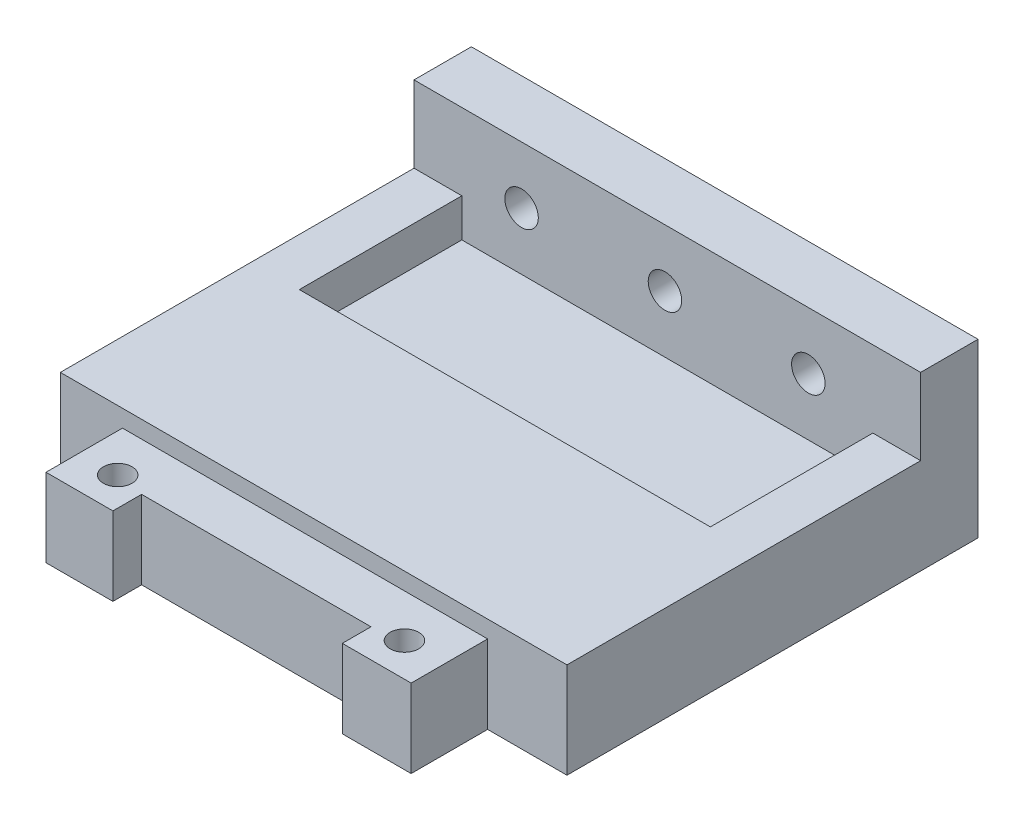
SolidWorks part; units mm, degrees
ref_plane "Front Plane" through (0, 0, 0) normal (0, 0, 1) x (1, 0, 0)
ref_plane "Top Plane" through (0, 0, 0) normal (0, 1, 0) x (1, 0, 0)
ref_plane "Right Plane" through (0, 0, 0) normal (1, 0, 0) x (0, 0, -1)
sketch "Sketch2" plane through (0, 0, 0) normal (0, 1, 0) x (1, 0, 0)
  line L1 (0, 0) -> (53, 0)
  line L2 (0, 0) -> (0, 43)
  line L3 (0, 43) -> (53, 43)
  line L4 (53, 0) -> (53, 43)
  dimension "D1" = 53
  dimension "D2" = 43
extrude "Boss-Extrude1" add sketch "Sketch2" along normal blind 10
sketch "Sketch3" plane through (0, 0, 0) normal (0, 0, 1) x (1, 0, 0)
  line L0 (0, 0) -> (53, 0) construction
  line L1 (6.499, 0) -> (44.699, 0)
  line L2 (6.499, 0) -> (6.499, 8.2)
  line L3 (6.499, 8.2) -> (44.699, 8.2)
  line L4 (44.699, 0) -> (44.699, 8.2)
  dimension "D1" = 38.2
  dimension "D2" = 8.2
extrude "Boss-Extrude2" add sketch "Sketch3" along normal blind 8
sketch "Sketch4" plane through (0, 0, 8) normal (0, 0, 1) x (1, 0, 0)
  line L0 (44.699, 8.2) -> (6.499, 8.2) construction
  line L1 (13.499, 8.2) -> (37.499, 8.2)
  line L2 (13.499, 8.2) -> (13.499, 0)
  line L3 (13.499, 0) -> (37.499, 0)
  line L4 (37.499, 8.2) -> (37.499, 0)
  line L5 (6.499, 0) -> (44.699, 0) construction
  line L6 (6.499, 8.2) -> (6.499, 0) construction
  dimension "D1" = 24
  dimension "D2" = 7
extrude "Cut-Extrude1" cut sketch "Sketch4" against normal blind 3 contours L1 L4 L3 L2
sketch "Sketch5" plane through (0, 8.2, 0) normal (0, 1, 0) x (1, 0, 0)
  line L0 (44.699, -8) -> (37.499, -8) construction
  line L1 (6.499, -8) -> (6.499, 0) construction
  circle A0 centre (40.499, -4.5) radius 1.5
  circle A1 centre (10.499, -4.5) radius 1.5
  point P0 (10.499, -4.5)
  point P1 (40.499, -4.5)
  point P2 (41.099, -8)
  dimension "D3" = 4
  dimension "D1" = 30
  dimension "D2" = 3.5
extrude "Cut-Extrude2" cut sketch "Sketch5" against normal through all
sketch "Sketch6" plane through (0, 10, 0) normal (0, 1, 0) x (1, 0, 0)
  line L0 (53, 0) -> (53, 43) construction
  line L1 (0, 43) -> (53, 43)
  line L2 (0, 43) -> (0, 37)
  line L3 (0, 37) -> (53, 37)
  line L4 (53, 43) -> (53, 37)
  dimension "D1" = 6
extrude "Boss-Extrude4" add sketch "Sketch6" along normal blind 8
sketch "Sketch7" plane through (0, 0, -43) normal (0, 0, -1) x (-1, 0, 0)
  line L0 (-53, 18) -> (0, 18) construction
  line L1 (0, 18) -> (0, 0) construction
  circle A0 centre (-41.25, 12) radius 1.75
  circle A1 centre (-26.25, 12) radius 1.75
  circle A2 centre (-11.25, 12) radius 1.75
  point P0 (-41.25, 12)
  point P1 (-26.25, 12)
  point P2 (-11.25, 12)
  dimension "D1" = 15
  dimension "D2" = 15
  dimension "D3" = 6
  dimension "D4" = 11.25
extrude "Cut-Extrude3" cut sketch "Sketch7" against normal through all
sketch "Sketch8" plane through (0, 10, 0) normal (0, 1, 0) x (1, 0, 0)
  line L0 (0, 37) -> (0, 0) construction
  line L1 (5, 37) -> (48, 37)
  line L2 (5, 37) -> (5, 20)
  line L3 (5, 20) -> (48, 20)
  line L4 (48, 37) -> (48, 20)
  line L5 (0, 37) -> (53, 37) construction
  line L7 (53, 0) -> (53, 37) construction
  line L8 (0, 0) -> (53, 0) construction
  dimension "D1" = 5
  dimension "D2" = 0
  dimension "D3" = 5
  dimension "D4" = 20
extrude "Cut-Extrude4" cut sketch "Sketch8" against normal blind 4
